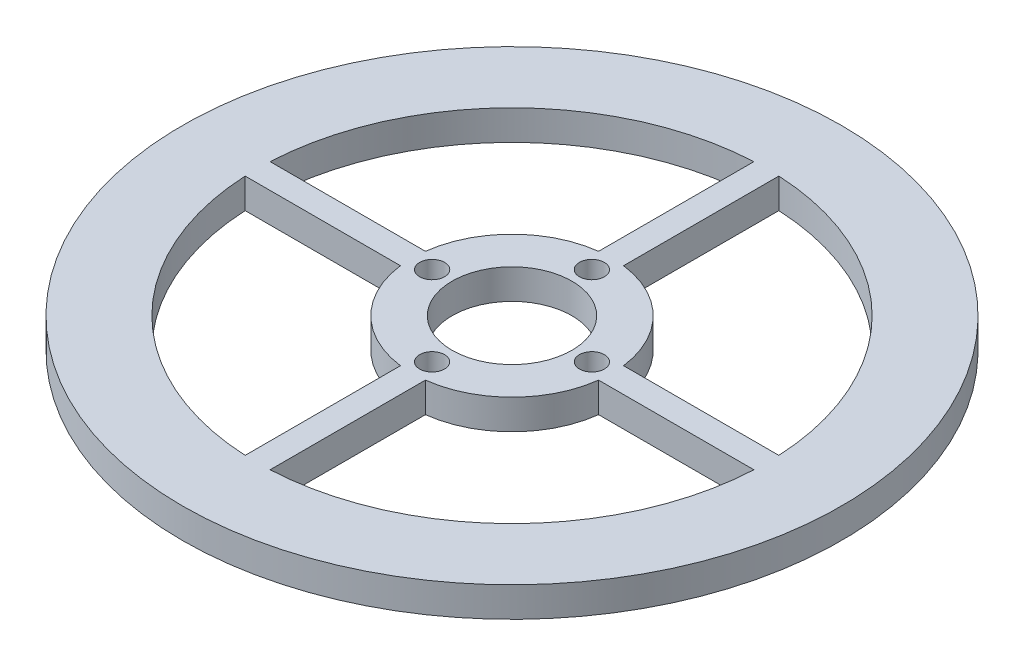
SolidWorks part; units mm, degrees
ref_plane "前视基准面" through (0, 0, 0) normal (0, 0, 1) x (1, 0, 0)
ref_plane "上视基准面" through (0, 0, 0) normal (0, 1, 0) x (1, 0, 0)
ref_plane "右视基准面" through (0, 0, 0) normal (1, 0, 0) x (0, 0, -1)
other "Configuration Table"
sketch "草图1" plane through (0, 0, 0) normal (0, 1, 0) x (1, 0, 0)
  line L0 (0, 0) -> (8, 0) construction
  line L1 (0, 0) -> (0, 8) construction
  line L2 (9.9216, 1.25) -> (25.4693, 1.25)
  line L3 (9.9216, -1.25) -> (25.4693, -1.25)
  line L4 (1.25, -9.9216) -> (1.25, -25.4693)
  line L5 (-1.25, -9.9216) -> (-1.25, -25.4693)
  line L6 (-9.9216, -1.25) -> (-25.4693, -1.25)
  line L7 (-9.9216, 1.25) -> (-25.4693, 1.25)
  line L8 (-1.25, 9.9216) -> (-1.25, 25.4693)
  line L9 (1.25, 9.9216) -> (1.25, 25.4693)
  circle A0 centre (0, 0) radius 33
  circle A1 centre (0, 0) radius 8 construction
  circle A2 centre (8, 0) radius 1.25
  circle A3 centre (0, -8) radius 1.25
  circle A4 centre (-8, 0) radius 1.25
  circle A5 centre (0, 8) radius 1.25
  circle A6 centre (0, 0) radius 6
  circle A7 centre (0, 0) radius 10
  circle A8 centre (0, 0) radius 25.5
  dimension "D1" = 66
  dimension "D2" = 16
  dimension "D3" = 2.5
  dimension "D5" = 12
  dimension "D6" = 20
  dimension "D7" = 51
  dimension "D8" = 2.5
  dimension "D4" = 4
  dimension "D9" = 4
extrude "凸台-拉伸1" add sketch "草图1" along normal blind 3
